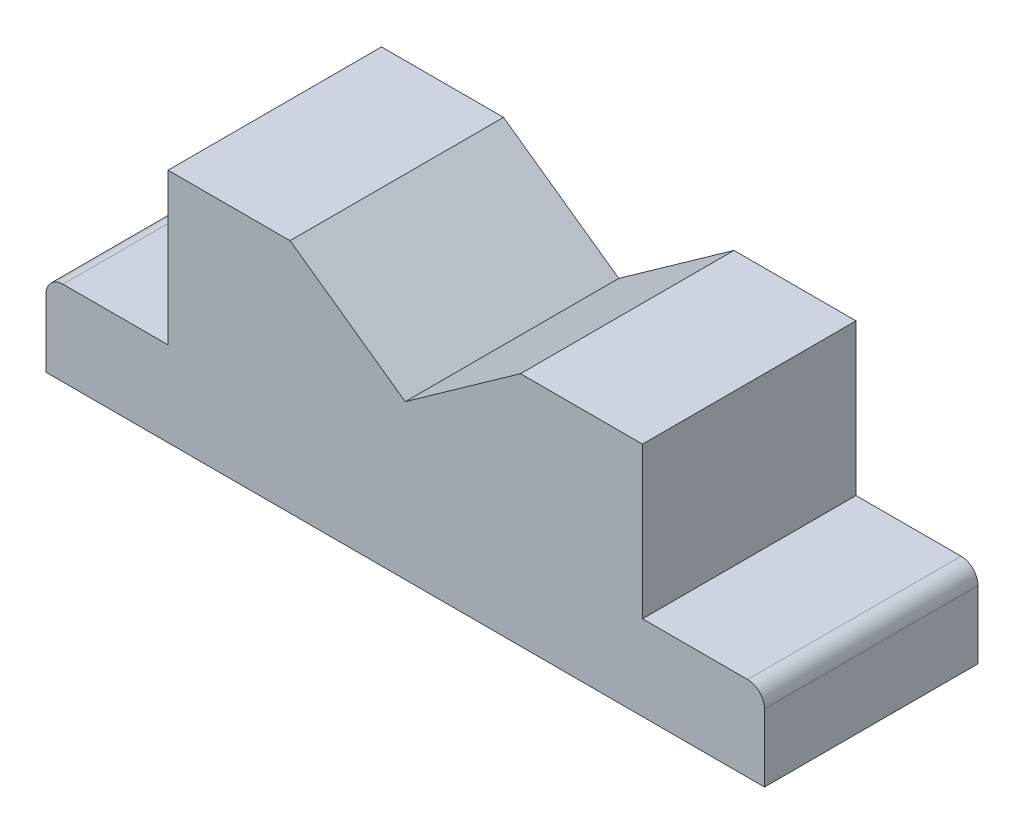
SolidWorks part; units mm, degrees
ref_plane "Front Plane" through (0, 0, 0) normal (0, 0, 1) x (1, 0, 0)
ref_plane "Top Plane" through (0, 0, 0) normal (0, 1, 0) x (1, 0, 0)
ref_plane "Right Plane" through (0, 0, 0) normal (1, 0, 0) x (0, 0, -1)
sketch "Sketch1" plane through (0, 0, 0) normal (0, 0, 1) x (1, 0, 0)
  line L0 (0, 0) -> (212, 0)
  line L1 (212, 0) -> (212, 25)
  line L2 (212, 25) -> (176, 25)
  line L3 (176, 25) -> (176, 69.6325)
  line L4 (176, 69.6325) -> (140, 69.6325)
  line L5 (0, 0) -> (0, 25)
  line L6 (0, 25) -> (36.0046, 25)
  line L7 (36.0046, 25) -> (36.0046, 69.6325)
  line L8 (36.0046, 69.6325) -> (72.0046, 69.6325)
  line L9 (72.0046, 69.6325) -> (106.0046, 45.4853)
  line L10 (106.0046, 45.4853) -> (140, 69.6325)
  dimension "D1" = 25
  dimension "D2" = 36.0046
  dimension "D3" = 36
  dimension "D4" = 36
  dimension "D5" = 212
  dimension "D6" = 25
  dimension "D7" = 36
  dimension "D8" = 34
extrude "Boss-Extrude1" add sketch "Sketch1" along normal blind 63
fillet "Fillet1" radius 5 1 edges at (212, 25, 31.5)
fillet "Fillet2" radius 5 1 edges at (0, 25, 31.5)
